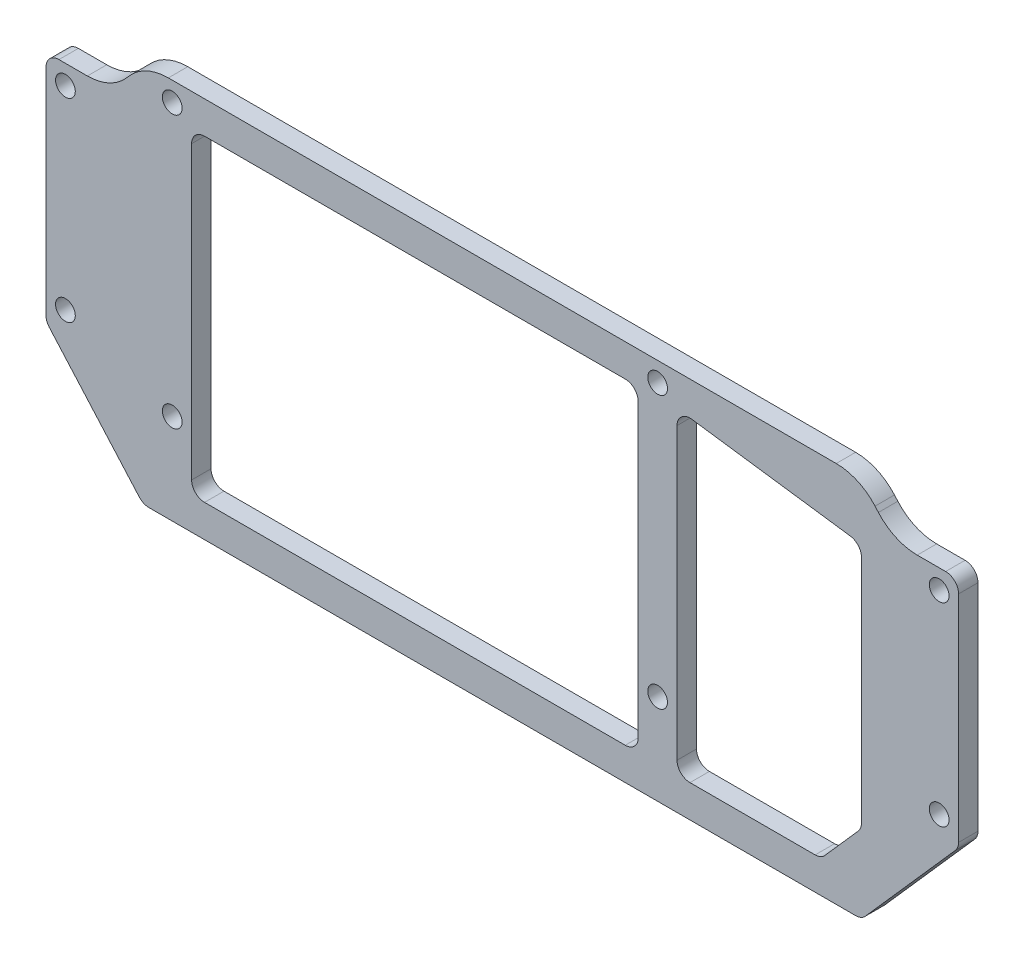
SolidWorks part; units mm, degrees
material "A-玻璃纤维"
ref_plane "前视基准面" through (0, 0, 0) normal (0, 0, 1) x (1, 0, 0)
ref_plane "上视基准面" through (0, 0, 0) normal (0, 1, 0) x (1, 0, 0)
ref_plane "右视基准面" through (0, 0, 0) normal (1, 0, 0) x (0, 0, -1)
other "Configuration Table"
sketch "草图1" plane through (0, 0, 0) normal (0, 0, 1) x (1, 0, 0)
  line L0 (-70.5, -18) -> (-70.5, 18)
  line L1 (-67.5, -15) -> (67.5, -15) construction
  line L2 (-67.5, -15) -> (-67.5, 15) construction
  line L3 (-67.5, 15) -> (67.5, 15) construction
  line L4 (67.5, -15) -> (67.5, 15) construction
  line L5 (-67.5, -15) -> (67.5, 15) construction
  line L6 (-67.5, 15) -> (67.5, -15) construction
  line L7 (-70.5, 18) -> (-55.5, 35)
  line L8 (-55.5, 35) -> (55.5, 35)
  line L9 (-70.5, 0) -> (0, 0) construction
  line L10 (0, 0) -> (0, 35) construction
  line L11 (-70.5, -18) -> (-55.5, -35)
  line L12 (-55.5, -35) -> (55.5, -35)
  line L13 (70.5, 18) -> (55.5, 35)
  line L14 (70.5, -18) -> (70.5, 18)
  line L15 (70.5, -18) -> (55.5, -35)
  circle A0 centre (67.5, -15) radius 1.525
  circle A1 centre (-67.5, -15) radius 1.525
  circle A2 centre (-67.5, 15) radius 1.525
  circle A3 centre (67.5, 15) radius 1.525
  point P0 (0, 0)
  point P22 (0, -35)
  dimension "D3" = 3.05
  dimension "D1" = 135
  dimension "D2" = 30
  dimension "D4" = 3
  dimension "D5" = 70
  dimension "D6" = 3
  dimension "D7" = 15
extrude "凸台-拉伸1" add sketch "草图1" along normal mid plane 3
sketch "草图2" plane through (0, 0, -1.5) normal (0, 0, -1) x (-1, 0, 0)
  circle A0 centre (-24, 21) radius 1.525 construction
  circle A1 centre (-24, -21) radius 1.525 construction
  circle A2 centre (51, 21) radius 1.525 construction
  circle A3 centre (51, -21) radius 1.525 construction
  circle A4 centre (-24, 21) radius 1.525
  circle A5 centre (-24, -21) radius 1.525
  circle A6 centre (51, 21) radius 1.525
  circle A7 centre (51, -21) radius 1.525
extrude "切除-拉伸1" cut sketch "草图2" against normal mid plane 42
sketch "草图3" plane through (0, 0, -1.5) normal (0, 0, -1) x (-1, 0, 0)
  line L0 (-70.5, 18) -> (-60.5, 18)
  line L1 (-60.5, 18) -> (-45.5, 35)
  line L2 (-55.5, 35) -> (55.5, 35) construction
  line L3 (-45.5, 35) -> (-55.5, 35)
  line L4 (-55.5, 35) -> (-70.5, 18)
  line L5 (0, 0) -> (0, 42.9242) construction
  line L6 (55.5, 35) -> (70.5, 18)
  line L7 (45.5, 35) -> (55.5, 35)
  line L8 (60.5, 18) -> (45.5, 35)
  line L9 (70.5, 18) -> (60.5, 18)
  dimension "D1" = 10
extrude "切除-拉伸2" cut sketch "草图3" against normal mid plane 22
sketch "草图4" plane through (0, 0, -1.5) normal (0, 0, -1) x (-1, 0, 0)
  line L0 (-55.2059, 24) -> (55.2059, 24)
  line L1 (-45.5, 35) -> (-60.5, 18) construction
  line L2 (60.5, 18) -> (45.5, 35) construction
  line L3 (-55.2059, 24) -> (-45.5, 35)
  line L4 (-45.5, 35) -> (45.5, 35)
  line L5 (45.5, 35) -> (55.2059, 24)
  circle A0 centre (51, 21) radius 1.525 construction
  dimension "D1" = 3
extrude "切除-拉伸3" cut sketch "草图4" against normal mid plane 22
fillet "圆角1" radius 8 4 edges at (-60.5, 18, 0) (-55.2059, 24, 0) (60.5, 18, 0) (55.2059, 24, 0)
sketch "草图5" plane through (0, 0, -1.5) normal (0, 0, -1) x (-1, 0, 0)
  line L0 (-24, 21) -> (51, -21) construction
  line L1 (13.5, 0) -> (13.5, -15.845) construction
  line L2 (51.5957, 24) -> (-51.5957, 24) construction
  line L3 (-21, -30) -> (48, -30)
  line L4 (-21, -30) -> (-21, 19)
  line L5 (-21, 19) -> (48, 19)
  line L6 (48, -30) -> (48, 19)
  line L7 (-21, -30) -> (48, 19) construction
  line L8 (-21, 19) -> (48, -30) construction
  line L9 (55.5, -35) -> (-55.5, -35) construction
  line L10 (-55.5, 15.141) -> (-27, 19.072)
  line L11 (-27, 19.072) -> (-27, -30)
  line L12 (-27, -30) -> (-49.2428, -30)
  line L13 (-49.2428, -30) -> (-55.5, -22.9085)
  line L14 (-55.5, -22.9085) -> (-55.5, 15.141)
  line L15 (-55.5, -35) -> (-70.5, -18) construction
  line L16 (-70.5, -18) -> (-70.5, 18) construction
  line L17 (-67.5, 15) -> (-24, 21) construction
  circle A0 centre (51, 21) radius 1.525 construction
  circle A1 centre (-24, -21) radius 1.525 construction
  point P6 (13.5, -5.5)
  dimension "D1" = 5
  dimension "D2" = 3
  dimension "D3" = 5
  dimension "D4" = 8
  dimension "D5" = 15
  dimension "D6" = 3
  dimension "D7" = 3
  dimension "D8" = 5
extrude "切除-拉伸4" cut sketch "草图5" against normal mid plane 22
fillet "圆角2" radius 2 9 edges at (55.5, 15.141, 0) (27, 19.072, 0) (55.5, -22.9085, 0) (-48, -30, 0) (21, -30, 0) (21, 19, 0) (-48, 19, 0) (49.2428, -30, 0) (27, -30, 0)
fillet "圆角3" radius 2 6 edges at (55.5, -35, 0) (-55.5, -35, 0) (-70.5, -18, 0) (-70.5, 18, 0) (70.5, -18, 0) (70.5, 18, 0)
equation "\"D3@草图5\"=\"D1@草图5\""
